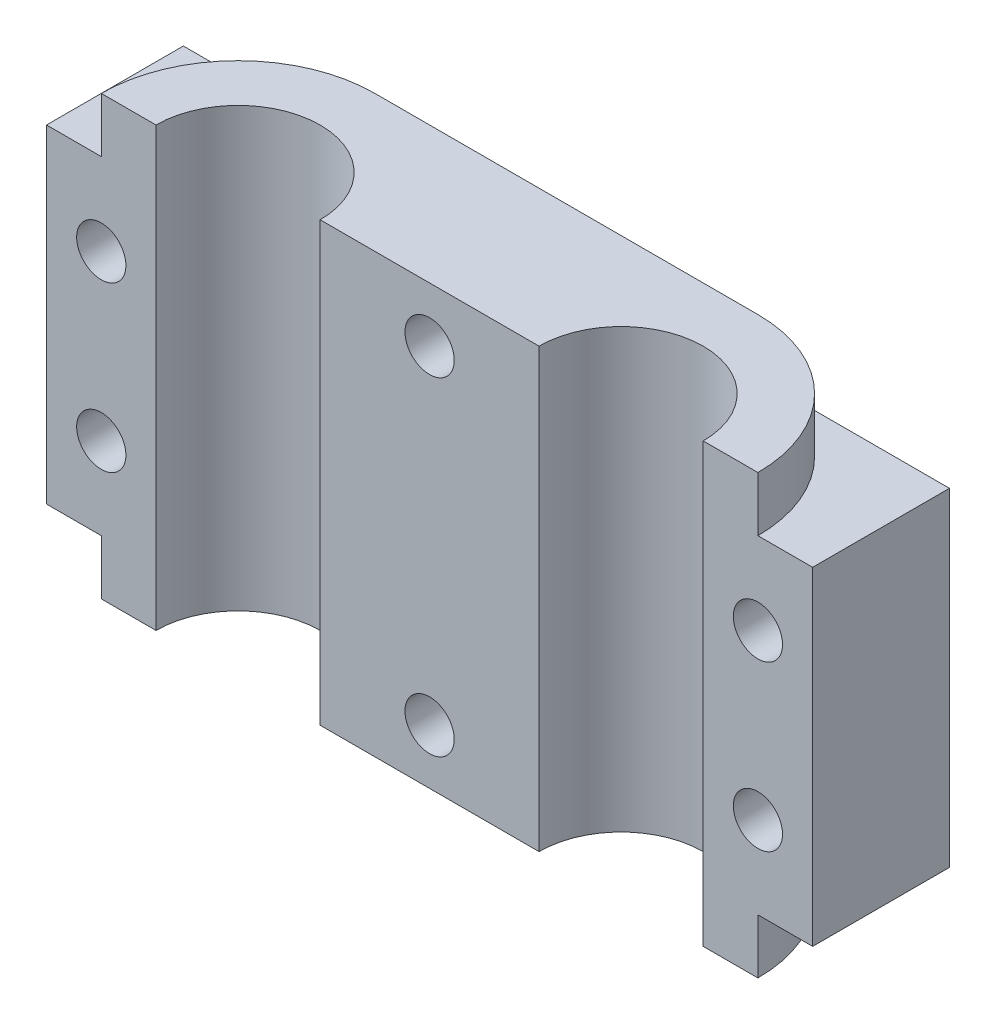
SolidWorks part; units mm, degrees
ref_plane "Front Plane" through (0, 0, 0) normal (0, 0, 1) x (1, 0, 0)
ref_plane "Top Plane" through (0, 0, 0) normal (0, 1, 0) x (1, 0, 0)
ref_plane "Right Plane" through (0, 0, 0) normal (1, 0, 0) x (0, 0, -1)
sketch "Sketch1" plane through (0, 0, 0) normal (0, 1, 0) x (1, 0, 0)
  line L0 (-35, -0.1163) -> (-35, -12.6163)
  line L1 (-35, -0.1163) -> (35, -0.1163)
  line L2 (-35, -12.6163) -> (-25, -12.6163)
  line L3 (-10, -12.6163) -> (10, -12.6163)
  line L4 (25, -12.6163) -> (35, -12.6163)
  line L5 (35, -12.6163) -> (35, -0.1163)
  arc A0 (-25, -12.6163) -> (-10, -12.6163) centre (-17.5, -12.6163) cw
  arc A1 (10, -12.6163) -> (25, -12.6163) centre (17.5, -12.6163) cw
  dimension "D4" = 7.5
  dimension "D1" = 12.5
  dimension "D2" = 70
  dimension "D3" = 35
  dimension "D5" = 35
extrude "Boss-Extrude1" add sketch "Sketch1" along normal mid plane 30
sketch "Sketch2" plane through (0, 15, 0) normal (0, 1, 0) x (1, 0, 0)
  line L0 (-17.5, -0.1163) -> (17.5, -0.1163)
  line L1 (-5, -12.6163) -> (5, -12.6163)
  line L2 (-30, -12.6163) -> (-25, -12.6163)
  line L3 (-10, -12.6163) -> (-5, -12.6163)
  line L4 (30, -12.6163) -> (25, -12.6163)
  line L5 (10, -12.6163) -> (5, -12.6163)
  arc A0 (-17.5, -0.1163) -> (-30, -12.6163) centre (-17.5, -12.6163) ccw
  arc A1 (30, -12.6163) -> (17.5, -0.1163) centre (17.5, -12.6163) ccw
  arc A2 (-25, -12.6163) -> (-10, -12.6163) centre (-17.5, -12.6163) cw
  arc A3 (25, -12.6163) -> (10, -12.6163) centre (17.5, -12.6163) ccw
  dimension "D1" = 25
extrude "Boss-Extrude2" add sketch "Sketch2" along normal blind 5 and the other way blind 35
sketch "Sketch3" plane through (0, 0, 12.6163) normal (0, 0, 1) x (1, 0, 0)
  line L0 (0, 20) -> (0, -20) construction
  line L1 (-10, 20) -> (10, 20) construction
  line L2 (-10, -20) -> (10, -20) construction
  line L3 (-35, 0) -> (35, 0) construction
  line L4 (-35, 15) -> (-35, -15) construction
  line L5 (35, 15) -> (35, -15) construction
  line L7 (-35, 15) -> (-30, 15) construction
  circle A0 centre (-30, 7.5) radius 2.25
  circle A1 centre (-30, -7.5) radius 2.25
  circle A2 centre (0, 15) radius 2.25
  circle A3 centre (30, -7.5) radius 2.25
  circle A4 centre (30, 7.5) radius 2.25
  circle A5 centre (0, -15) radius 2.25
  dimension "D4" = 4.5
  dimension "D1" = 15
  dimension "D2" = 7.5
  dimension "D3" = 5
  dimension "D5" = 30
  dimension "D6" = 30
extrude "Cut-Extrude1" cut sketch "Sketch3" against normal through all
